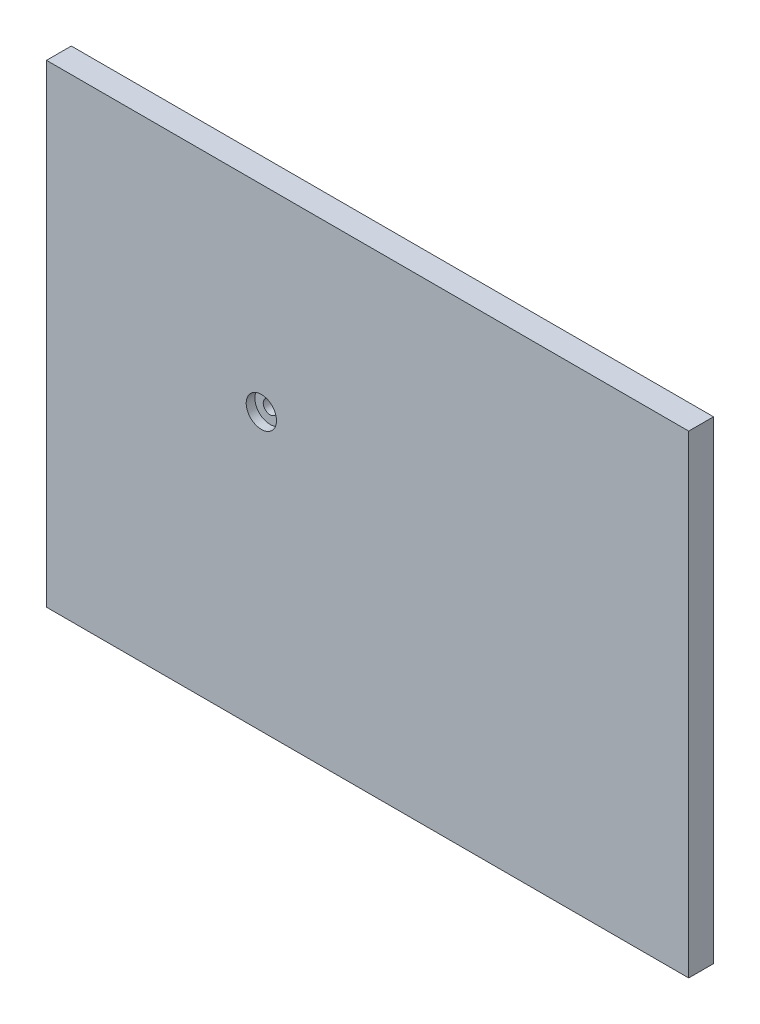
SolidWorks part; units mm, degrees
material "ABS PC"
ref_plane "Front Plane" through (0, 0, 0) normal (0, 0, 1) x (1, 0, 0)
ref_plane "Top Plane" through (0, 0, 0) normal (0, 1, 0) x (1, 0, 0)
ref_plane "Right Plane" through (0, 0, 0) normal (1, 0, 0) x (0, 0, -1)
sketch "Sketch1" plane through (0, 0, 0) normal (0, 0, 1) x (1, 0, 0)
  line L1 (-129.5455, 95.5451) -> (129.5455, 95.5451)
  line L2 (-129.5455, 95.5451) -> (-129.5455, -95.5451)
  line L3 (-129.5455, -95.5451) -> (129.5455, -95.5451)
  line L4 (129.5455, 95.5451) -> (129.5455, -95.5451)
  line L5 (-129.5455, 95.5451) -> (129.5455, -95.5451) construction
  line L6 (-129.5455, -95.5451) -> (129.5455, 95.5451) construction
  point P0 (0, 0)
extrude "Boss-Extrude1" add sketch "Sketch1" along normal blind 10
sketch "Sketch4" plane through (0, 0, 10) normal (0, 0, 1) x (1, 0, 0)
  point P0 (-42.861, 16.035)
hole_wizard "CBORE for M5 Hex Head Bolt1" positions "Sketch4" profile "Sketch3" counterbore size "M5" standard "ISO" end condition through all
sketch "Sketch3" plane through (-42.861, 16.035, 10) normal (1, 0, 0) x (0, -1, 0)
  line L0 (0, 0) -> (0, 10)
  line L1 (0, 10) -> (2.75, 10)
  line L3 (2.75, 10) -> (2.75, 3.5)
  line L4 (2.75, 3.5) -> (6.119, 3.5)
  line L5 (6.119, 3.5) -> (6.119, 0)
  line L7 (6.119, 0) -> (0, 0)
  line L11 (0, -6.35) -> (0, 107.95) construction
  dimension "Thru Hole Dia." = 5.5
  dimension "Thru Hole Depth" = 10
  dimension "C'Bore Dia." = 12.238
  dimension "C'Bore Depth" = 3.5
